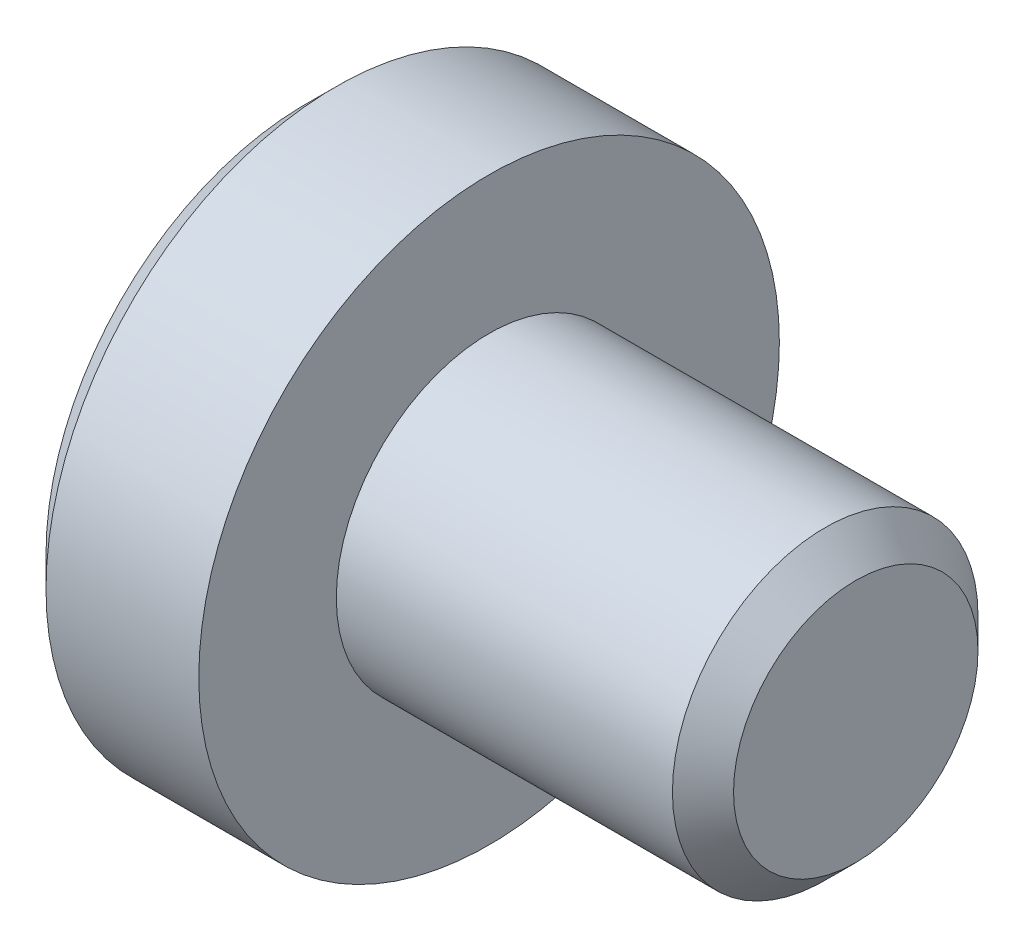
SolidWorks part; units mm, degrees
material "AISI 4130 Steel, normalized at 870C"
ref_plane "Front Plane" through (0, 0, 0) normal (0, 0, 1) x (1, 0, 0)
ref_plane "Top Plane" through (0, 0, 0) normal (0, 1, 0) x (1, 0, 0)
ref_plane "Right Plane" through (0, 0, 0) normal (1, 0, 0) x (0, 0, -1)
sketch "Sketch1" plane through (0, 0, 0) normal (0, 0, 1) x (1, 0, 0)
  line L0 (0, 0) -> (0, 4.75)
  line L1 (0, 4.75) -> (3, 4.75)
  line L2 (3, 4.75) -> (3, 2.5)
  line L3 (3, 2.5) -> (9, 2.5)
  line L4 (9, 2.5) -> (9, 0)
  line L5 (9, 0) -> (0, 0)
  dimension "D1" = 4.75
  dimension "D2" = 6
  dimension "D3" = 2.5
  dimension "D4" = 3
revolve "Revolve1" add sketch "Sketch1" angle 360 about L5
cosmetic thread "Cosmetic Thread1" parameters "D1"=4, "D2"=4.11
sketch "Sketch2" plane through (0, 0, 0) normal (-1, 0, 0) x (0, 0, 1)
  line L0 (0, 0) -> (0, 2.3094) construction
  line L1 (0, 2.3094) -> (-2, 1.1547)
  line L2 (-2, 1.1547) -> (-2, -1.1547)
  line L3 (-2, -1.1547) -> (0, -2.3094)
  line L4 (0, -2.3094) -> (2, -1.1547)
  line L5 (2, -1.1547) -> (2, 1.1547)
  line L6 (2, 1.1547) -> (0, 2.3094)
  circle A0 centre (0, 0) radius 2 construction
  dimension "D1" = 4
extrude "Cut-Extrude1" cut sketch "Sketch2" against normal blind 2.75
chamfer "Chamfer1" distance 0.5 angle 45 1 edges at (9, 0, -2.5)
chamfer "Chamfer2" distance 0.5 angle 45 1 edges at (0, 0, -4.75)
